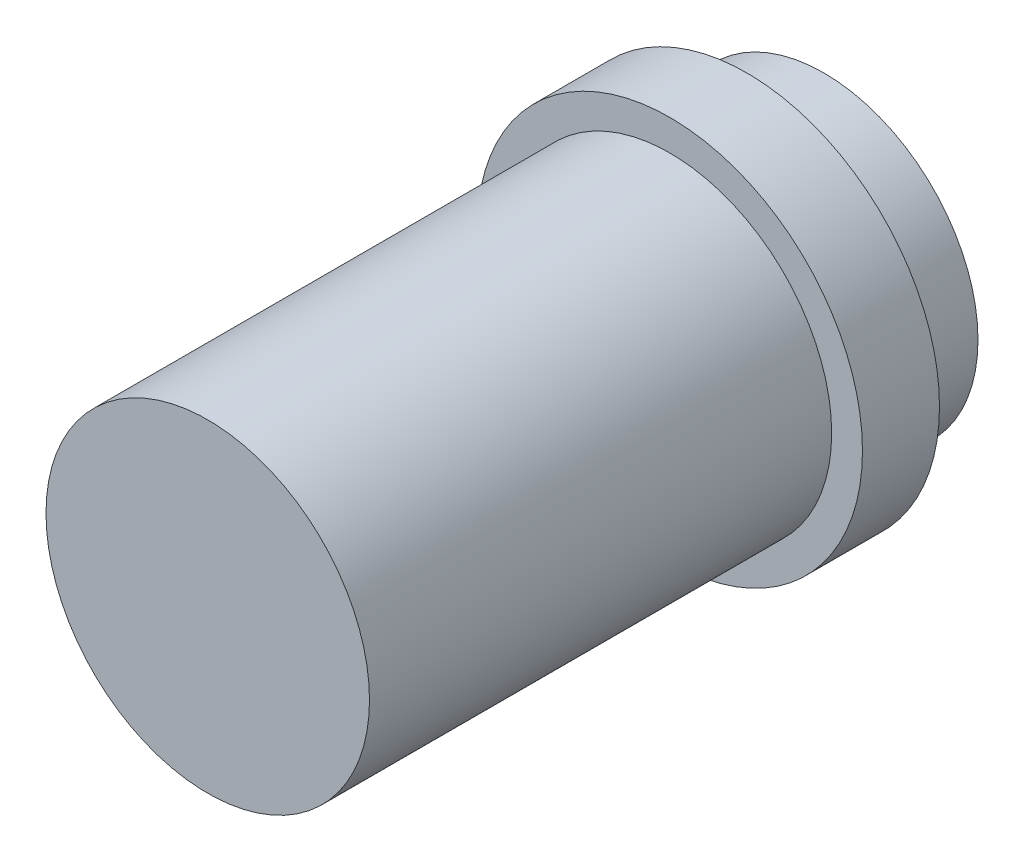
SolidWorks part; units mm, degrees
ref_plane "前视基准面" through (0, 0, 0) normal (0, 0, 1) x (1, 0, 0)
ref_plane "上视基准面" through (0, 0, 0) normal (0, 1, 0) x (1, 0, 0)
ref_plane "右视基准面" through (0, 0, 0) normal (1, 0, 0) x (0, 0, -1)
sketch "草图1" plane through (0, 0, 0) normal (0, 0, 1) x (1, 0, 0)
  circle A0 centre (0, 0) radius 1.25
  circle A1 centre (0, 0) radius 2.5
  dimension "内径" = 2.5
  dimension "外径" = 5
extrude "凸台-拉伸1" add sketch "草图1" along normal blind 1
sketch "草图2" plane through (0, 0, 0) normal (0, 0, -1) x (-1, 0, 0)
  circle A0 centre (0, 0) radius 1.25 construction
  circle A1 centre (0, 0) radius 1.25
  circle A2 centre (0, 0) radius 2
  dimension "外径" = 4
extrude "凸台-拉伸2" add sketch "草图2" along normal blind 1
sketch "草图4" plane through (0, 0, 1) normal (0, 0, 1) x (1, 0, 0)
  circle A0 centre (0, 0) radius 2.1
  circle A1 centre (0, 0) radius 1.25 construction
  circle A2 centre (0, 0) radius 1.25
  dimension "外径" = 4.2
extrude "凸台-拉伸3" add sketch "草图4" along normal blind 6
sketch "草图3" plane through (0, 0, 7) normal (0, 0, 1) x (1, 0, 0)
  circle A0 centre (0, 0) radius 2.1 construction
  circle A2 centre (0, 0) radius 2.1
  point P3 (0, 0)
extrude "凸台-拉伸4" add sketch "草图3" against normal blind 1
